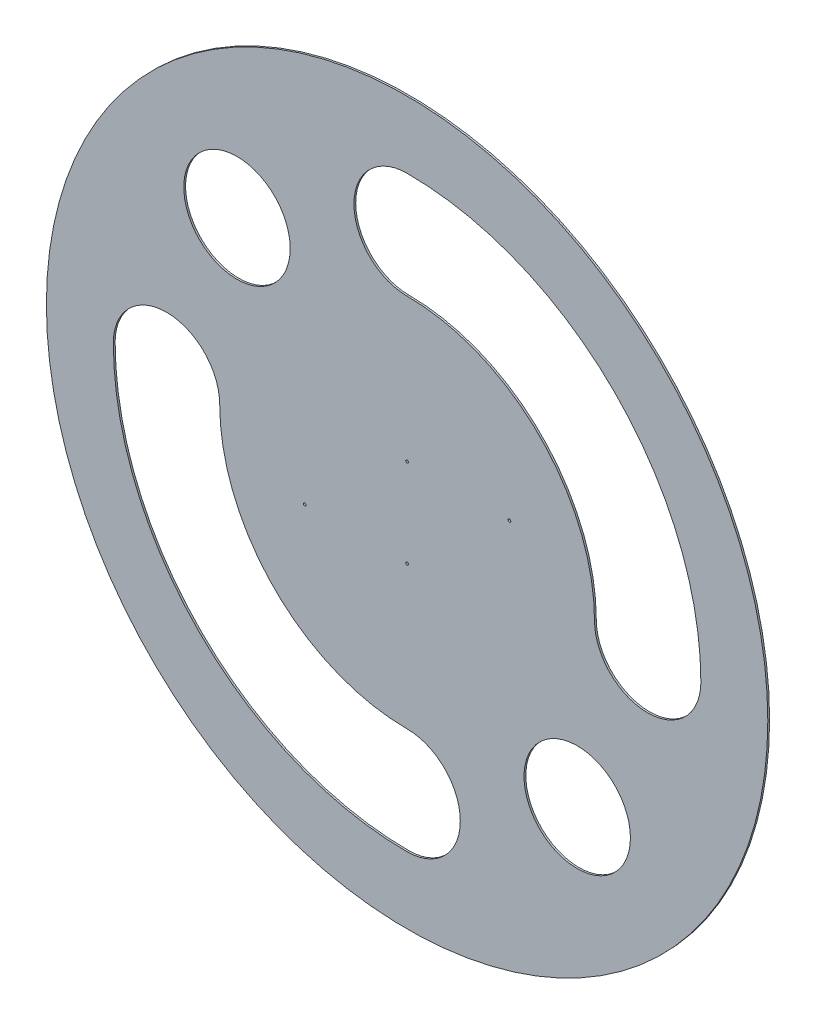
SolidWorks part; units mm, degrees
ref_plane "前视基准面" through (0, 0, 0) normal (0, 0, 1) x (1, 0, 0)
ref_plane "上视基准面" through (0, 0, 0) normal (0, 1, 0) x (1, 0, 0)
ref_plane "右视基准面" through (0, 0, 0) normal (1, 0, 0) x (0, 0, -1)
sketch "草图1" plane through (0, 0, 0) normal (0, 0, 1) x (1, 0, 0)
  line L0 (0, -49) -> (-113.5, -49) construction
  line L1 (0, 49) -> (113.5, 49) construction
  line L2 (0, 49) -> (0, -49) construction
  line L3 (0, 0) -> (-282.8427, 282.8427) construction
  line L4 (0, 0) -> (188.6455, -188.6455) construction
  circle A0 centre (0, 0) radius 400
  circle A5 centre (0, 0) radius 49 construction
  circle A6 centre (0, -49) radius 1.5
  circle A7 centre (0, 49) radius 1.5
  circle A11 centre (-113.5, -49) radius 1.5
  circle A12 centre (113.5, 49) radius 1.5
  arc A13 (-266.785, 0) -> (0, -266.785) centre (0, 0) ccw construction
  arc A14 (-325.7637, 0) -> (0, -325.7637) centre (0, 0) ccw
  arc A15 (-207.8063, 0) -> (0, -207.8063) centre (0, 0) ccw
  arc A16 (-207.8063, 0) -> (-325.7637, 0) centre (-266.785, 0) ccw
  arc A17 (0, -325.7637) -> (0, -207.8063) centre (0, -266.785) ccw
  arc A18 (0, 266.785) -> (266.785, 0) centre (0, 0) cw construction
  arc A19 (0, 325.7637) -> (325.7637, 0) centre (0, 0) cw
  arc A20 (0, 207.8063) -> (207.8063, 0) centre (0, 0) cw
  arc A21 (0, 207.8063) -> (0, 325.7637) centre (0, 266.785) cw
  arc A22 (325.7637, 0) -> (207.8063, 0) centre (266.785, 0) cw
  circle A23 centre (0, 0) radius 266.785 construction
  circle A24 centre (-188.6455, 188.6455) radius 59
  circle A25 centre (188.6455, -188.6455) radius 59
  point P14 (-188.6455, -188.6455)
  point P23 (188.6455, 188.6455)
  dimension "D1" = 98
extrude "凸台-拉伸1" add sketch "草图1" along normal blind 2
